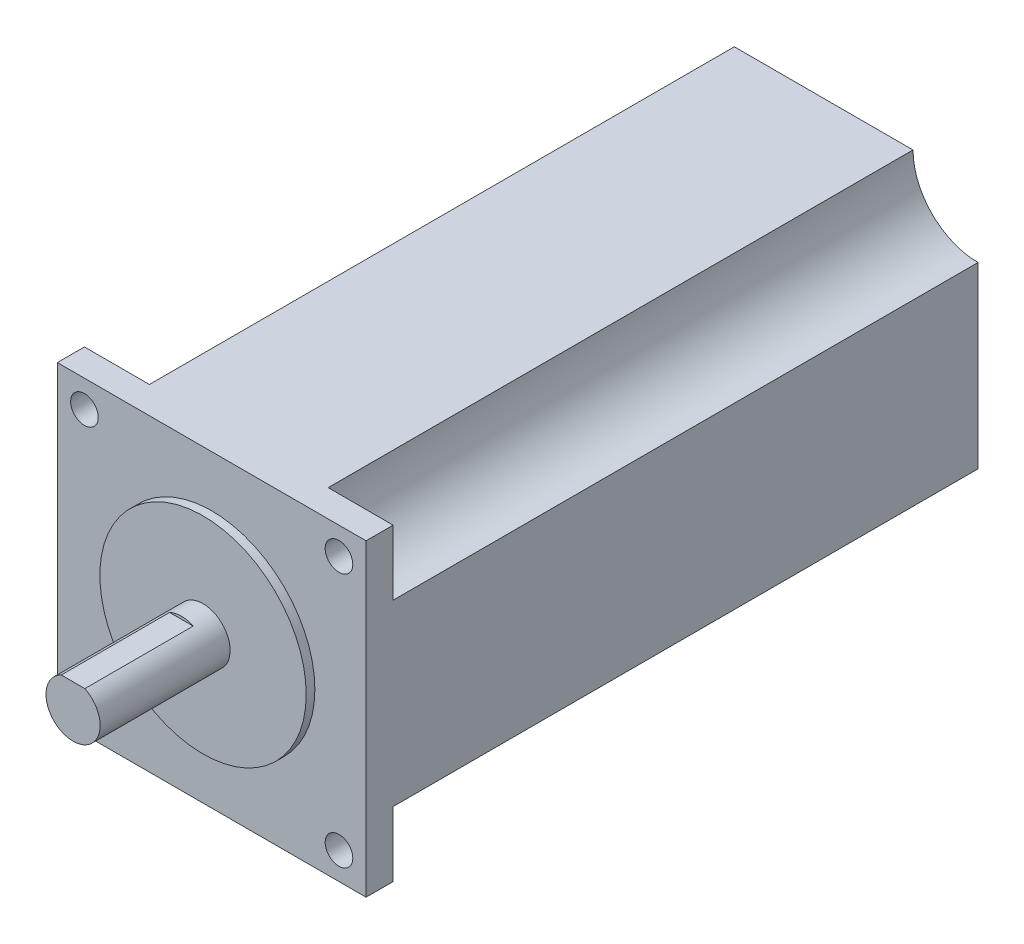
SolidWorks part; units mm, degrees
ref_plane "Plan de face" through (0, 0, 0) normal (0, 0, 1) x (1, 0, 0)
ref_plane "Plan de dessus" through (0, 0, 0) normal (0, 1, 0) x (1, 0, 0)
ref_plane "Plan de droite" through (0, 0, 0) normal (1, 0, 0) x (0, 0, -1)
sketch "Esquisse1" plane through (0, 0, 0) normal (0, 0, 1) x (1, 0, 0)
  line L0 (-38.8542, 4.541) -> (18.1458, -52.459) construction
  line L1 (-38.8542, 4.541) -> (18.1458, 4.541)
  line L2 (-38.8542, 4.541) -> (-38.8542, -52.459)
  line L3 (-38.8542, -52.459) -> (18.1458, -52.459)
  line L4 (18.1458, 4.541) -> (18.1458, -52.459)
  line L5 (-33.8542, -47.459) -> (13.1458, -0.459) construction
  circle A0 centre (-33.8542, -0.459) radius 2.55
  circle A1 centre (13.1458, -0.459) radius 2.55
  circle A2 centre (13.1458, -47.459) radius 2.55
  circle A3 centre (-33.8542, -47.459) radius 2.55
  point P14 (-10.3542, -23.959)
  point P15 (-10.3542, -23.959)
  dimension "D2" = 5.1
  dimension "D1" = 57
  dimension "D3" = 47
extrude "Boss.-Extru.1" add sketch "Esquisse1" along normal blind 5
sketch "Esquisse2" plane through (0, 0, 0) normal (0, 0, -1) x (-1, 0, 0)
  line L0 (-6.1458, 4.541) -> (26.8542, 4.541)
  line L1 (-18.1458, 4.541) -> (38.8542, 4.541) construction
  line L2 (-18.1458, -7.459) -> (-18.1458, -40.459)
  line L3 (-18.1458, -52.459) -> (-18.1458, 4.541) construction
  line L4 (-6.1458, -52.459) -> (26.8542, -52.459)
  line L5 (38.8542, -52.459) -> (-18.1458, -52.459) construction
  line L6 (38.8542, -7.459) -> (38.8542, -40.459)
  line L7 (38.8542, 4.541) -> (38.8542, -52.459) construction
  line L8 (26.8542, 4.541) -> (26.8542, -7.459) construction
  line L9 (26.8542, -7.459) -> (38.8542, -7.459) construction
  line L10 (38.8542, -40.459) -> (26.8542, -40.459) construction
  line L11 (26.8542, -40.459) -> (26.8542, -52.459) construction
  line L12 (-6.1458, 4.541) -> (-6.1458, -7.459) construction
  line L13 (-6.1458, -7.459) -> (-18.1458, -7.459) construction
  line L14 (-18.1458, -40.459) -> (-6.1458, -40.459) construction
  line L15 (-6.1458, -40.459) -> (-6.1458, -52.459) construction
  arc A0 (-18.1458, -7.459) -> (-6.1458, 4.541) centre (-18.1458, 4.541) ccw
  arc A1 (26.8542, 4.541) -> (38.8542, -7.459) centre (38.8542, 4.541) ccw
  arc A2 (-6.1458, -52.459) -> (-18.1458, -40.459) centre (-18.1458, -52.459) ccw
  arc A3 (26.8542, -52.459) -> (38.8542, -40.459) centre (38.8542, -52.459) cw
  dimension "D1" = 12
extrude "Boss.-Extru.2" add sketch "Esquisse2" along normal blind 108
sketch "Esquisse3" plane through (0, 0, 5) normal (0, 0, 1) x (1, 0, 0)
  line L0 (-38.8542, 4.541) -> (18.1458, -52.459) construction
  circle A0 centre (-10.3542, -23.959) radius 19.05
  dimension "D1" = 38.1
extrude "Boss.-Extru.3" add sketch "Esquisse3" along normal blind 1.6
sketch "Esquisse4" plane through (0, 0, 6.6) normal (0, 0, 1) x (1, 0, 0)
  circle A0 centre (-10.3542, -23.959) radius 5
  dimension "D1" = 10
extrude "Boss.-Extru.4" add sketch "Esquisse4" along normal blind 4
sketch "Esquisse5" plane through (0, 0, 10.6) normal (0, 0, 1) x (1, 0, 0)
  line L0 (-12.5337, -19.459) -> (-8.1748, -19.459)
  circle A0 centre (-10.3542, -23.959) radius 5 construction
  arc A1 (-8.1748, -19.459) -> (-12.5337, -19.459) centre (-10.3542, -23.959) cw
  point P7 (-10.3542, -28.959)
  dimension "D1" = 9.5
extrude "Boss.-Extru.5" add sketch "Esquisse5" along normal blind 20
